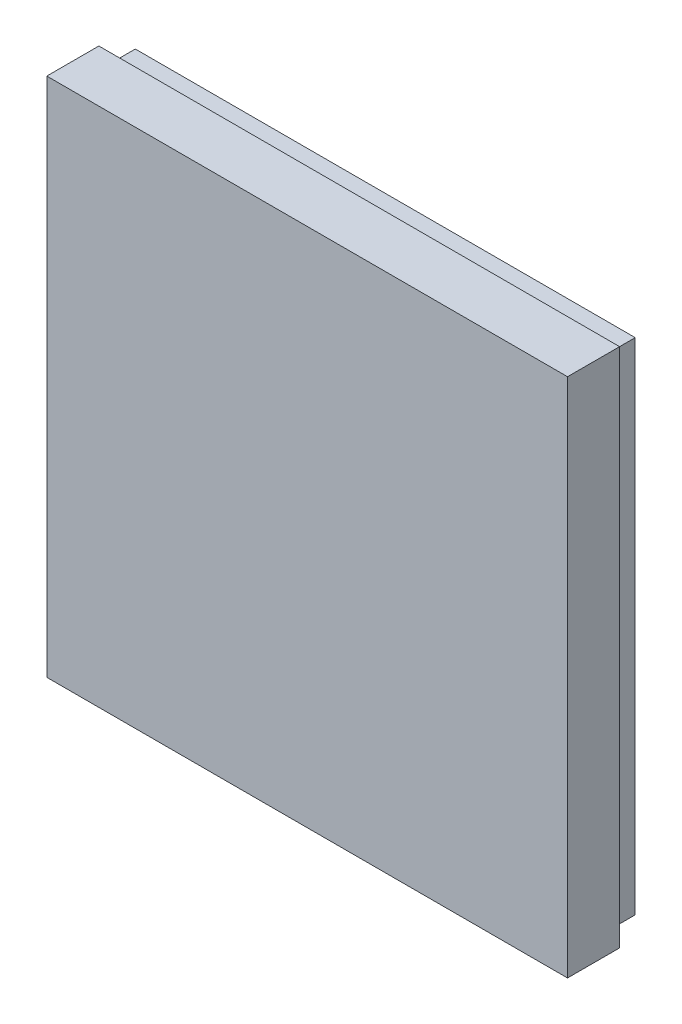
SolidWorks part; units mm, degrees
ref_plane "Front" through (0, 0, 0) normal (0, 0, 1) x (1, 0, 0)
ref_plane "Top" through (0, 0, 0) normal (0, 1, 0) x (1, 0, 0)
ref_plane "Right" through (0, 0, 0) normal (1, 0, 0) x (0, 0, -1)
other "Configuration Table"
sketch "Sketch1" plane through (0, 0, 0) normal (0, 0, 1) x (1, 0, 0)
  line L1 (-75.8471, 30.4577) -> (24.1529, 30.4577)
  line L2 (-75.8471, 30.4577) -> (-75.8471, -69.5423)
  line L3 (-75.8471, -69.5423) -> (24.1529, -69.5423)
  line L4 (24.1529, 30.4577) -> (24.1529, -69.5423)
  dimension "D1" = 100
  dimension "D2" = 100
extrude "Boss-Extrude1" add sketch "Sketch1" along normal blind 10
sketch "Sketch2" plane through (0, 0, 0) normal (0, 0, -1) x (-1, 0, 0)
  line L0 (-24.1529, 30.4577) -> (75.8471, 30.4577) construction
  line L1 (-22.1529, 28.4577) -> (73.8471, 28.4577)
  line L2 (-22.1529, 28.4577) -> (-22.1529, -67.5423)
  line L3 (-22.1529, -67.5423) -> (73.8471, -67.5423)
  line L4 (73.8471, 28.4577) -> (73.8471, -67.5423)
  line L5 (-24.1529, -69.5423) -> (-24.1529, 30.4577) construction
  line L6 (75.8471, -69.5423) -> (-24.1529, -69.5423) construction
  line L7 (75.8471, 30.4577) -> (75.8471, -69.5423) construction
  dimension "D1" = 2
  dimension "D2" = 2
  dimension "D3" = 2
  dimension "D4" = 2
extrude "Boss-Extrude2" add sketch "Sketch2" along normal blind 5
